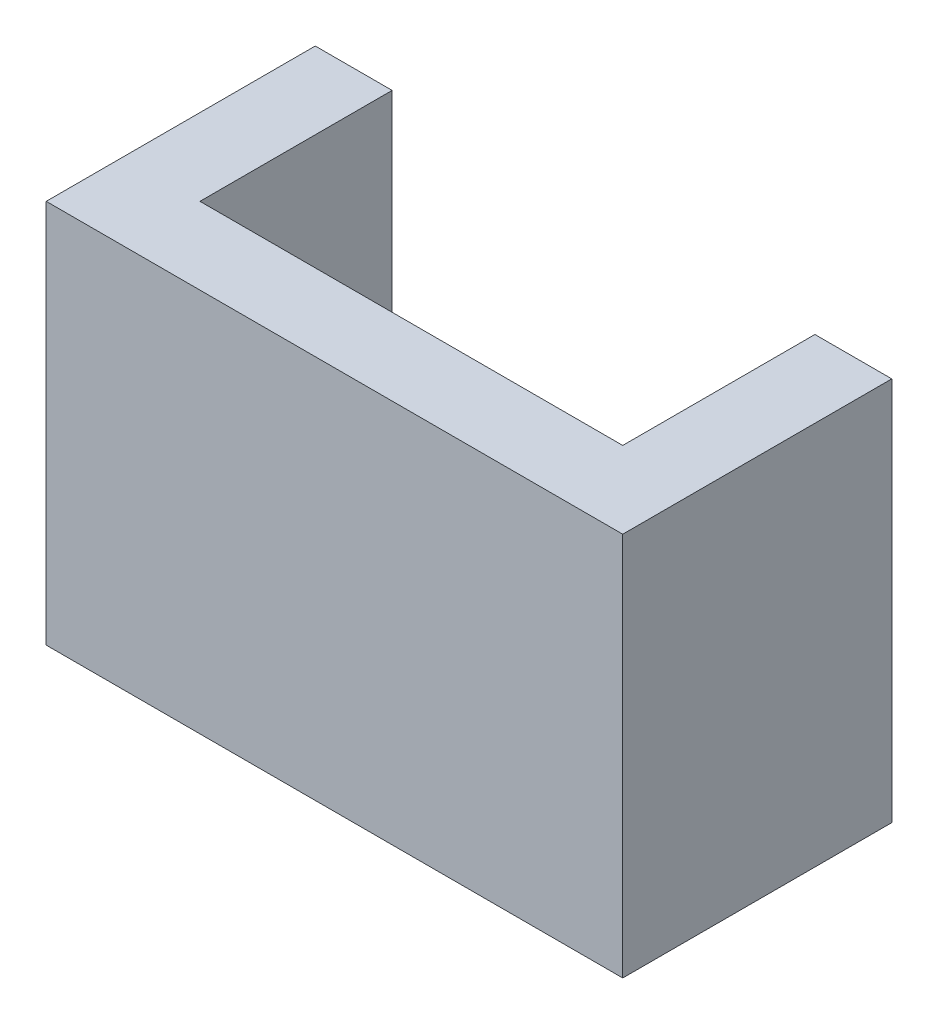
SolidWorks part; units mm, degrees
ref_plane "Front Plane" through (0, 0, 0) normal (0, 0, 1) x (1, 0, 0)
ref_plane "Top Plane" through (0, 0, 0) normal (0, 1, 0) x (1, 0, 0)
ref_plane "Right Plane" through (0, 0, 0) normal (1, 0, 0) x (0, 0, -1)
sketch "Sketch1" plane through (0, 0, 0) normal (0, 0, 1) x (1, 0, 0)
  line L1 (-7.1778, 3.92) -> (7.8222, 3.92)
  line L2 (-7.1778, 3.92) -> (-7.1778, -6.08)
  line L3 (-7.1778, -6.08) -> (7.8222, -6.08)
  line L4 (7.8222, 3.92) -> (7.8222, -6.08)
  dimension "D1" = 15
  dimension "D2" = 10
extrude "Boss-Extrude1" add sketch "Sketch1" along normal blind 7
sketch "Sketch2" plane through (0, 3.92, 0) normal (0, 1, 0) x (1, 0, 0)
  line L0 (7.8222, 0) -> (-7.1778, 0) construction
  line L1 (-5.1778, 0) -> (5.8222, 0)
  line L2 (-5.1778, 0) -> (-5.1778, -5)
  line L3 (-5.1778, -5) -> (5.8222, -5)
  line L4 (5.8222, 0) -> (5.8222, -5)
  line L5 (-7.1778, -7) -> (-7.1778, 0) construction
  line L6 (7.8222, -7) -> (-7.1778, -7) construction
  line L7 (7.8222, -7) -> (7.8222, 0) construction
  dimension "D1" = 2
  dimension "D2" = 2
  dimension "D3" = 2
extrude "Cut-Extrude1" cut sketch "Sketch2" against normal up to surface (10 mm away) up to face at (0.3222, -6.08, 3.5)
